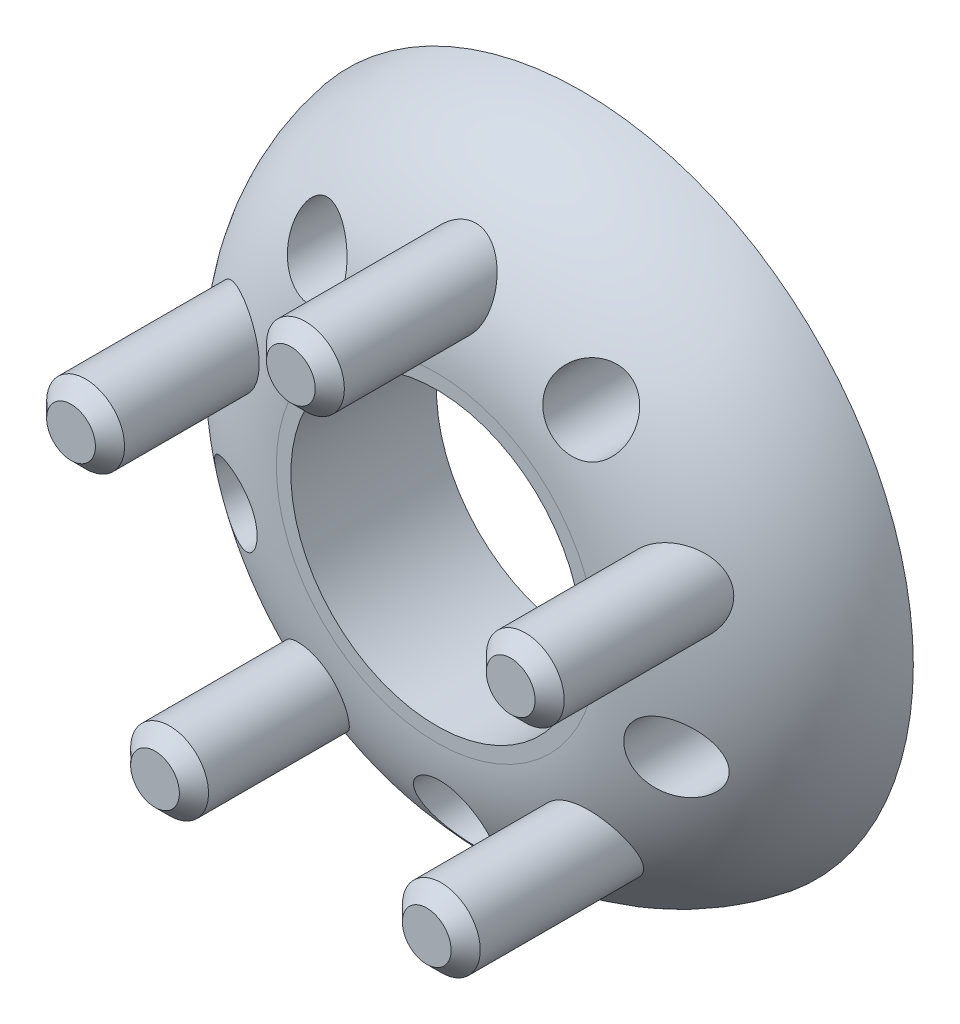
SolidWorks part; units mm, degrees
material "ABS"
ref_plane "Front Plane" through (0, 0, 0) normal (0, 0, 1) x (1, 0, 0)
ref_plane "Top Plane" through (0, 0, 0) normal (0, 1, 0) x (1, 0, 0)
ref_plane "Right Plane" through (0, 0, 0) normal (1, 0, 0) x (0, 0, -1)
sketch "스케치2" plane through (0, 0, 0) normal (1, 0, 0) x (0, 0, -1)
  line L1 (0, 0) -> (0, 11)
  line L2 (10, 22.7515) -> (10, 0)
  line L4 (10, 0) -> (0, 0) construction
  line L5 (0, 0) -> (10, 0)
  line L6 (7.5, 0) -> (7.5, 22.06) construction
  arc A2 (10, 22.7515) -> (0, 11) centre (11.9049, 11) ccw
  dimension "D3" = 11.9049
  dimension "D1" = 10
  dimension "D2" = 7.5
  dimension "D5" = 11
revolve "회전1" add sketch "스케치2" angle 360 about L4
sketch "Sketch8" plane through (0, 0, -10) normal (0, 0, -1) x (-1, 0, 0)
  line L10 (0, 15.875) -> (0, 0) construction
  circle A0 centre (0, 0) radius 13.2 construction
  circle A1 centre (0, 0) radius 18.55 construction
  circle A2 centre (0, 15.875) radius 2.675
  dimension "D1" = 26.4
  dimension "D2" = 37.1
extrude "Boss-Extrude3" add sketch "Sketch8" against normal offset from surface (20 mm away) 10 up to plane "Front Plane" offset beyond the face yes
sketch "Sketch9" plane through (0, 0, 10) normal (0, 0, 1) x (1, 0, 0)
  line L0 (0, 0) -> (-50000, 0) construction
  line L1 (0, 15.875) -> (0, 0) construction
  line L2 (0, 15.875) -> (0, -15.875) construction
  circle A2 centre (0, -15.875) radius 2.5
  dimension "D1" = 5
chamfer "Chamfer1" distance 1 angle 45 1 edges at (2.675, 15.875, 10)
extrude "컷-돌출2" cut sketch "Sketch9" against normal through all
sketch "스케치3" plane through (0, 0, 0) normal (0, 0, 1) x (1, 0, 0)
  circle A0 centre (0, 0) radius 10
  dimension "D1" = 20
extrude "컷-돌출3" cut sketch "스케치3" against normal through all
pattern_circular "원형 패턴2" count 5 over 360 about axis through (0, 0, 0) along (0, 0, 1) of "컷-돌출2", "Chamfer1", "Boss-Extrude3"
